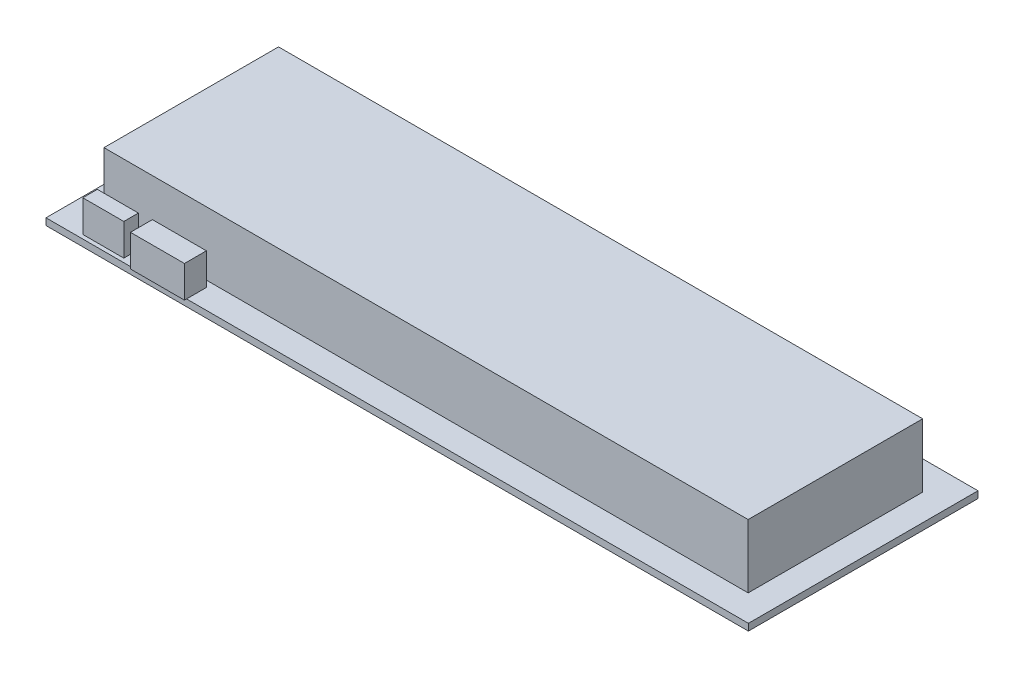
SolidWorks part; units mm, degrees
ref_plane "Front Plane" through (0, 0, 0) normal (0, 0, 1) x (1, 0, 0)
ref_plane "Top Plane" through (0, 0, 0) normal (0, 1, 0) x (1, 0, 0)
ref_plane "Right Plane" through (0, 0, 0) normal (1, 0, 0) x (0, 0, -1)
sketch "Sketch1" plane through (0, 0, 0) normal (0, 1, 0) x (1, 0, 0)
  line L1 (0, 0) -> (265.36, 0)
  line L2 (0, 0) -> (0, 86.74)
  line L3 (0, 86.74) -> (265.36, 86.74)
  line L4 (265.36, 0) -> (265.36, 86.74)
  dimension "D1" = 265.36
  dimension "D2" = 86.74
extrude "Boss-Extrude1" add sketch "Sketch1" along normal blind 2.56
sketch "Sketch2" plane through (0, 2.56, 0) normal (0, 1, 0) x (1, 0, 0)
  line L0 (0, 0) -> (265.36, 0) construction
  line L1 (12, 9.9) -> (255.36, 9.9)
  line L2 (12, 9.9) -> (12, 75.84)
  line L3 (12, 75.84) -> (255.36, 75.84)
  line L4 (255.36, 9.9) -> (255.36, 75.84)
  line L5 (0, 86.74) -> (0, 0) construction
  line L6 (265.36, 0) -> (265.36, 86.74) construction
  line L7 (265.36, 86.74) -> (0, 86.74) construction
  dimension "D1" = 9.9
  dimension "D2" = 12
  dimension "D3" = 10
  dimension "D4" = 10.9
extrude "Boss-Extrude2" add sketch "Sketch2" along normal blind 24
sketch "Sketch3" plane through (0, 2.56, 0) normal (0, 1, 0) x (1, 0, 0)
  line L0 (0, 86.74) -> (0, 0) construction
  line L1 (12.4, 1.5) -> (27.9, 1.5)
  line L2 (12.4, 1.5) -> (12.4, 7)
  line L3 (12.4, 7) -> (27.9, 7)
  line L4 (27.9, 1.5) -> (27.9, 7)
  line L5 (32.7, 7.5) -> (53.1, 7.5)
  line L6 (32.7, 7.5) -> (32.7, -0.8)
  line L7 (32.7, -0.8) -> (53.1, -0.8)
  line L8 (53.1, 7.5) -> (53.1, -0.8)
  line L9 (0, 0) -> (265.36, 0) construction
  dimension "D1" = 12.4
  dimension "D2" = 1.5
  dimension "D3" = 15.5
  dimension "D4" = 5.5
  dimension "D5" = 4.8
  dimension "D6" = 20.4
  dimension "D7" = 8.3
  dimension "D8" = 0.8
extrude "Boss-Extrude3" add sketch "Sketch3" along normal blind 12
